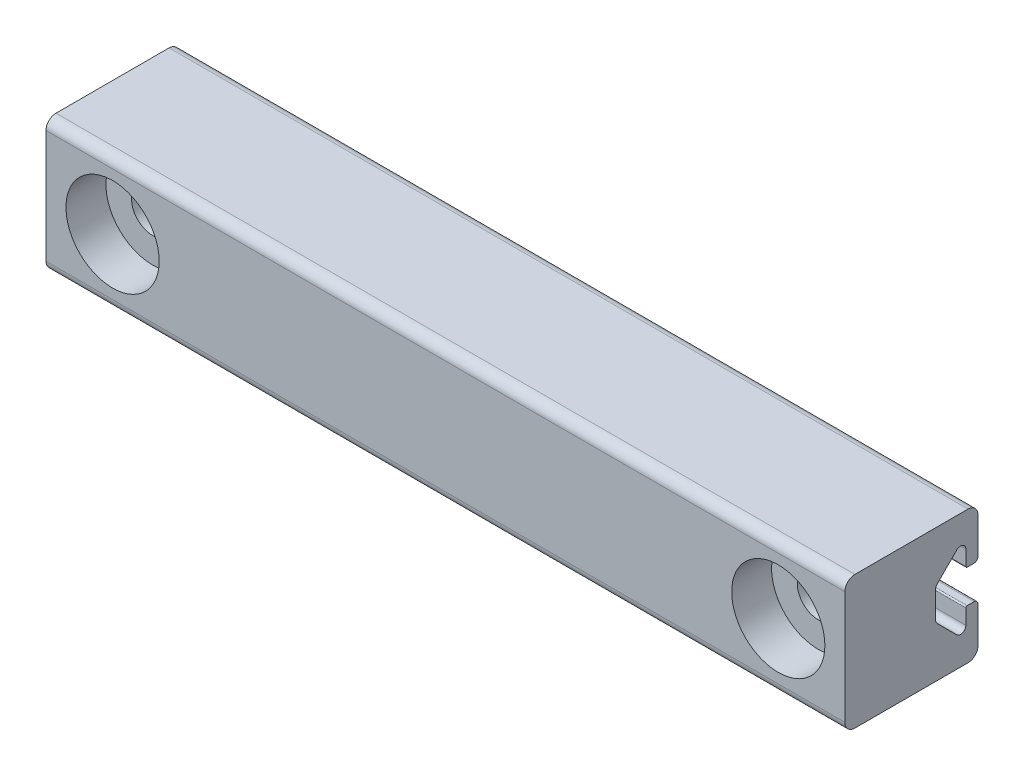
SolidWorks part; units mm, degrees
ref_plane "Front Plane" through (0, 0, 0) normal (0, 0, 1) x (1, 0, 0)
ref_plane "Top Plane" through (0, 0, 0) normal (0, 1, 0) x (1, 0, 0)
ref_plane "Right Plane" through (0, 0, 0) normal (1, 0, 0) x (0, 0, -1)
sketch "Sketch1" plane through (0, 0, 0) normal (1, 0, 0) x (0, 0, -1)
  line L0 (0, -10) -> (0, 10) construction
  line L1 (10, -10) -> (-10, -10)
  line L2 (10, -10) -> (10, 10)
  line L3 (10, 10) -> (0, 10)
  line L4 (-10, -10) -> (-10, 10)
  line L5 (10, -10) -> (-10, 10) construction
  line L6 (10, 10) -> (-10, -10) construction
  line L7 (10, 0) -> (-10, 0) construction
  line L8 (-2.5, 9.4) -> (-2.5, 8.3731)
  line L9 (-2.7, 8.1731) -> (-4.95, 8.1731)
  line L10 (-5.5157, 6.8075) -> (-2.6011, 3.8929)
  line L11 (-1.894, 3.6) -> (0, 3.6)
  line L12 (-5.3502, 4.0584) -> (-4.0584, 5.3502) construction
  line L13 (-3.825, 8.1731) -> (-3.825, 10) construction
  line L14 (-3.1, 10) -> (-10, 10)
  line L15 (-5.75, 7.3731) -> (5.75, 7.3731) construction
  circle A0 centre (0, 0) radius 2.15
  arc A1 (-4.95, 8.1731) -> (-5.5157, 6.8075) centre (-4.95, 7.3731) ccw
  arc A2 (-2.6011, 3.8929) -> (-1.894, 3.6) centre (-1.894, 4.6) ccw
  arc A3 (-2.5, 8.3731) -> (-2.7, 8.1731) centre (-2.7, 8.3731) cw
  arc A4 (-2.5, 9.4) -> (-3.1, 10) centre (-3.1, 9.4) ccw
  point P0 (0, 0)
  point P9 (0, 0)
  point P12 (0, 0)
  point P22 (-4.7043, 4.7043)
  point P32 (-2.5, 10)
  point P33 (-2.5, 8.8866)
  point P35 (-4.0584, 5.3502)
  point P37 (0, 7.3731)
  dimension "Center Hole Diameter" = 4.3
  dimension "D4" = 1
  dimension "D5" = 0.2
  dimension "D6" = 0.6
  dimension "D3" = 0.8
  dimension "Rail Height" = 20
  dimension "D7" = 6.4
  dimension "T Slot Width" = 5
  dimension "D10" = 10
  dimension "Rail Width" = 20
  dimension "D2" = 11.5
sketch "Sketch2" plane through (0, 0, 0) normal (0, 0, 1) x (1, 0, 0)
  line L0 (-132.4, 10) -> (-132.4, -10) construction
  line L1 (152.4, -10) -> (-152.4, -10) construction
  line L2 (152.4, -10) -> (152.4, 10) construction
  line L3 (152.4, 10) -> (-152.4, 10) construction
  line L4 (-152.4, -10) -> (-152.4, 10) construction
  line L5 (152.4, -10) -> (-152.4, 10) construction
  line L6 (152.4, 10) -> (-152.4, -10) construction
  line L7 (132.4, 10) -> (132.4, -10) construction
  point P0 (0, 0)
  point P12 (132.4, 0)
  dimension "Length" = 304.8
  dimension "D1" = 20
  dimension "D2" = 20
sketch "Sketch3" plane through (0, 0, 0) normal (1, 0, 0) x (0, 0, -1)
  line L0 (-5.5157, 6.8075) -> (-2.6011, 3.8929) construction
  line L5 (-3.1, 10) -> (-10, 10) construction
  line L6 (-2.5, 9.4) -> (-2.5, 8.3731) construction
  line L7 (-2.7, 8.1731) -> (-4.95, 8.1731) construction
  line L8 (-1.894, 3.6) -> (0, 3.6) construction
  line L9 (-5.5157, 6.8075) -> (-2.6011, 3.8929)
  line L10 (-10, 10) -> (0, 0) construction
  line L12 (-3.6, 1.894) -> (-3.6, 0)
  line L13 (-8.1731, 2.7) -> (-8.1731, 4.95)
  line L14 (-3.1, 10) -> (-8.5, 10)
  line L15 (-2.5, 9.4) -> (-2.5, 8.3731)
  line L16 (-2.7, 8.1731) -> (-4.95, 8.1731)
  line L17 (-1.894, 3.6) -> (0, 3.6)
  line L18 (-9.4, 2.5) -> (-8.3731, 2.5)
  line L19 (-10, 3.1) -> (-10, 8.5)
  line L20 (-6.8075, 5.5157) -> (-3.8929, 2.6011)
  line L21 (-3.6, 0) -> (-2.15, 0)
  line L22 (0, 3.6) -> (0, 2.15)
  arc A0 (-2.5, 9.4) -> (-3.1, 10) centre (-3.1, 9.4) ccw construction
  arc A1 (-2.7, 8.1731) -> (-2.5, 8.3731) centre (-2.7, 8.3731) ccw construction
  arc A2 (-4.95, 8.1731) -> (-5.5157, 6.8075) centre (-4.95, 7.3731) ccw construction
  arc A3 (-2.6011, 3.8929) -> (-1.894, 3.6) centre (-1.894, 4.6) ccw construction
  arc A4 (-2.5, 9.4) -> (-3.1, 10) centre (-3.1, 9.4) ccw
  arc A5 (-2.7, 8.1731) -> (-2.5, 8.3731) centre (-2.7, 8.3731) ccw
  arc A6 (-4.95, 8.1731) -> (-5.5157, 6.8075) centre (-4.95, 7.3731) ccw
  arc A7 (-2.6011, 3.8929) -> (-1.894, 3.6) centre (-1.894, 4.6) ccw
  arc A8 (-3.8929, 2.6011) -> (-3.6, 1.894) centre (-4.6, 1.894) cw
  arc A9 (-8.1731, 4.95) -> (-6.8075, 5.5157) centre (-7.3731, 4.95) cw
  arc A10 (-8.1731, 2.7) -> (-8.3731, 2.5) centre (-8.3731, 2.7) cw
  arc A11 (-9.4, 2.5) -> (-10, 3.1) centre (-9.4, 3.1) cw
  circle A12 centre (0, 0) radius 2.15 construction
  arc A13 (0, 2.15) -> (-2.15, 0) centre (0, 0) ccw
  arc A14 (-10, 8.5) -> (-8.5, 10) centre (-8.5, 8.5) cw
  dimension "D1" = 1.5
extrude "Boss-Extrude1" add sketch "Sketch3" against normal up to vertex (152.4 mm away) and the other way up to vertex (152.4 mm away) up to point (-152.4, 10, 0) other way up to point (152.4, 10, 0)
mirror "Mirror1" about plane through (0, 0, 0) normal (0, 1, 0) of bodies 104
mirror "Mirror2" about plane through (0, 0, 0) normal (0, 0, 1) of bodies 105
sketch "Sketch4" plane through (152.4, 0, 0) normal (1, 0, 0) x (0, 0, -1)
  line L36 (1.894, 3.6) -> (-1.894, 3.6)
  line L37 (-2.6011, 3.8929) -> (-5.5157, 6.8075)
  line L38 (-4.95, 8.1731) -> (-2.7, 8.1731)
  line L39 (-2.5, 8.3731) -> (-2.5, 9.4)
  line L40 (-3.1, 10) -> (-8.5, 10)
  line L41 (-10, 8.5) -> (-10, 3.1)
  line L42 (-9.4, 2.5) -> (-8.3731, 2.5)
  line L43 (-8.1731, 2.7) -> (-8.1731, 4.95)
  line L44 (-6.8075, 5.5157) -> (-3.8929, 2.6011)
  line L45 (-3.6, 1.894) -> (-3.6, -1.894)
  line L46 (-3.8929, -2.6011) -> (-6.8075, -5.5157)
  line L47 (-8.1731, -4.95) -> (-8.1731, -2.7)
  line L48 (-8.3731, -2.5) -> (-9.4, -2.5)
  line L49 (-10, -3.1) -> (-10, -8.5)
  line L50 (-8.5, -10) -> (-3.1, -10)
  line L51 (-2.5, -9.4) -> (-2.5, -8.3731)
  line L52 (-2.7, -8.1731) -> (-4.95, -8.1731)
  line L53 (-5.5157, -6.8075) -> (-2.6011, -3.8929)
  line L54 (-1.894, -3.6) -> (1.894, -3.6)
  line L55 (2.6011, -3.8929) -> (5.5157, -6.8075)
  line L56 (4.95, -8.1731) -> (2.7, -8.1731)
  line L57 (2.5, -8.3731) -> (2.5, -9.4)
  line L58 (3.1, -10) -> (8.5, -10)
  line L59 (10, -8.5) -> (10, -3.1)
  line L60 (9.4, -2.5) -> (8.3731, -2.5)
  line L61 (8.1731, -2.7) -> (8.1731, -4.95)
  line L62 (6.8075, -5.5157) -> (3.8929, -2.6011)
  line L63 (3.6, -1.894) -> (3.6, 1.894)
  line L64 (3.8929, 2.6011) -> (6.8075, 5.5157)
  line L65 (8.1731, 4.95) -> (8.1731, 2.7)
  line L66 (8.3731, 2.5) -> (9.4, 2.5)
  line L67 (10, 3.1) -> (10, 8.5)
  line L68 (8.5, 10) -> (3.1, 10)
  line L69 (2.5, 9.4) -> (2.5, 8.3731)
  line L70 (2.7, 8.1731) -> (4.95, 8.1731)
  line L71 (5.5157, 6.8075) -> (2.6011, 3.8929)
  line L72 (1.894, 3.6) -> (-1.894, 3.6)
  line L73 (-2.6011, 3.8929) -> (-5.5157, 6.8075)
  line L74 (-4.95, 8.1731) -> (-2.7, 8.1731)
  line L75 (-2.5, 8.3731) -> (-2.5, 9.4)
  line L76 (-3.1, 10) -> (-8.5, 10)
  line L77 (-10, 8.5) -> (-10, 3.1)
  line L78 (-9.4, 2.5) -> (-8.3731, 2.5)
  line L79 (-8.1731, 2.7) -> (-8.1731, 4.95)
  line L80 (-6.8075, 5.5157) -> (-3.8929, 2.6011)
  line L81 (-3.6, 1.894) -> (-3.6, -1.894)
  line L82 (-3.8929, -2.6011) -> (-6.8075, -5.5157)
  line L83 (-8.1731, -4.95) -> (-8.1731, -2.7)
  line L84 (-8.3731, -2.5) -> (-9.4, -2.5)
  line L85 (-10, -3.1) -> (-10, -8.5)
  line L86 (-8.5, -10) -> (-3.1, -10)
  line L87 (-2.5, -9.4) -> (-2.5, -8.3731)
  line L88 (-2.7, -8.1731) -> (-4.95, -8.1731)
  line L89 (-5.5157, -6.8075) -> (-2.6011, -3.8929)
  line L90 (-1.894, -3.6) -> (1.894, -3.6)
  line L91 (2.6011, -3.8929) -> (5.5157, -6.8075)
  line L92 (4.95, -8.1731) -> (2.7, -8.1731)
  line L93 (2.5, -8.3731) -> (2.5, -9.4)
  line L94 (3.1, -10) -> (8.5, -10)
  line L95 (10, -8.5) -> (10, -3.1)
  line L96 (9.4, -2.5) -> (8.3731, -2.5)
  line L97 (8.1731, -2.7) -> (8.1731, -4.95)
  line L98 (6.8075, -5.5157) -> (3.8929, -2.6011)
  line L99 (3.6, -1.894) -> (3.6, 1.894)
  line L100 (3.8929, 2.6011) -> (6.8075, 5.5157)
  line L101 (8.1731, 4.95) -> (8.1731, 2.7)
  line L102 (8.3731, 2.5) -> (9.4, 2.5)
  line L103 (10, 3.1) -> (10, 8.5)
  line L104 (8.5, 10) -> (3.1, 10)
  line L105 (2.5, 9.4) -> (2.5, 8.3731)
  line L106 (2.7, 8.1731) -> (4.95, 8.1731)
  line L107 (5.5157, 6.8075) -> (2.6011, 3.8929)
  circle A0 centre (0, 0) radius 2.15 construction
  circle A1 centre (0, 0) radius 2.15
  arc A36 (1.894, 3.6) -> (2.6011, 3.8929) centre (1.894, 4.6) ccw
  arc A37 (-2.6011, 3.8929) -> (-1.894, 3.6) centre (-1.894, 4.6) ccw
  arc A38 (-4.95, 8.1731) -> (-5.5157, 6.8075) centre (-4.95, 7.3731) ccw
  arc A39 (-2.7, 8.1731) -> (-2.5, 8.3731) centre (-2.7, 8.3731) ccw
  arc A40 (-2.5, 9.4) -> (-3.1, 10) centre (-3.1, 9.4) ccw
  arc A41 (-8.5, 10) -> (-10, 8.5) centre (-8.5, 8.5) ccw
  arc A42 (-10, 3.1) -> (-9.4, 2.5) centre (-9.4, 3.1) ccw
  arc A43 (-8.3731, 2.5) -> (-8.1731, 2.7) centre (-8.3731, 2.7) ccw
  arc A44 (-6.8075, 5.5157) -> (-8.1731, 4.95) centre (-7.3731, 4.95) ccw
  arc A45 (-3.6, 1.894) -> (-3.8929, 2.6011) centre (-4.6, 1.894) ccw
  arc A46 (-3.8929, -2.6011) -> (-3.6, -1.894) centre (-4.6, -1.894) ccw
  arc A47 (-8.1731, -4.95) -> (-6.8075, -5.5157) centre (-7.3731, -4.95) ccw
  arc A48 (-8.1731, -2.7) -> (-8.3731, -2.5) centre (-8.3731, -2.7) ccw
  arc A49 (-9.4, -2.5) -> (-10, -3.1) centre (-9.4, -3.1) ccw
  arc A50 (-10, -8.5) -> (-8.5, -10) centre (-8.5, -8.5) ccw
  arc A51 (-3.1, -10) -> (-2.5, -9.4) centre (-3.1, -9.4) ccw
  arc A52 (-2.5, -8.3731) -> (-2.7, -8.1731) centre (-2.7, -8.3731) ccw
  arc A53 (-5.5157, -6.8075) -> (-4.95, -8.1731) centre (-4.95, -7.3731) ccw
  arc A54 (-1.894, -3.6) -> (-2.6011, -3.8929) centre (-1.894, -4.6) ccw
  arc A55 (2.6011, -3.8929) -> (1.894, -3.6) centre (1.894, -4.6) ccw
  arc A56 (4.95, -8.1731) -> (5.5157, -6.8075) centre (4.95, -7.3731) ccw
  arc A57 (2.7, -8.1731) -> (2.5, -8.3731) centre (2.7, -8.3731) ccw
  arc A58 (2.5, -9.4) -> (3.1, -10) centre (3.1, -9.4) ccw
  arc A59 (8.5, -10) -> (10, -8.5) centre (8.5, -8.5) ccw
  arc A60 (10, -3.1) -> (9.4, -2.5) centre (9.4, -3.1) ccw
  arc A61 (8.3731, -2.5) -> (8.1731, -2.7) centre (8.3731, -2.7) ccw
  arc A62 (6.8075, -5.5157) -> (8.1731, -4.95) centre (7.3731, -4.95) ccw
  arc A63 (3.6, -1.894) -> (3.8929, -2.6011) centre (4.6, -1.894) ccw
  arc A64 (3.8929, 2.6011) -> (3.6, 1.894) centre (4.6, 1.894) ccw
  arc A65 (8.1731, 4.95) -> (6.8075, 5.5157) centre (7.3731, 4.95) ccw
  arc A66 (8.1731, 2.7) -> (8.3731, 2.5) centre (8.3731, 2.7) ccw
  arc A67 (9.4, 2.5) -> (10, 3.1) centre (9.4, 3.1) ccw
  arc A68 (10, 8.5) -> (8.5, 10) centre (8.5, 8.5) ccw
  arc A69 (3.1, 10) -> (2.5, 9.4) centre (3.1, 9.4) ccw
  arc A70 (2.5, 8.3731) -> (2.7, 8.1731) centre (2.7, 8.3731) ccw
  arc A71 (5.5157, 6.8075) -> (4.95, 8.1731) centre (4.95, 7.3731) ccw
  arc A72 (1.894, 3.6) -> (2.6011, 3.8929) centre (1.894, 4.6) ccw
  arc A73 (-2.6011, 3.8929) -> (-1.894, 3.6) centre (-1.894, 4.6) ccw
  arc A74 (-4.95, 8.1731) -> (-5.5157, 6.8075) centre (-4.95, 7.3731) ccw
  arc A75 (-2.7, 8.1731) -> (-2.5, 8.3731) centre (-2.7, 8.3731) ccw
  arc A76 (-2.5, 9.4) -> (-3.1, 10) centre (-3.1, 9.4) ccw
  arc A77 (-8.5, 10) -> (-10, 8.5) centre (-8.5, 8.5) ccw
  arc A78 (-10, 3.1) -> (-9.4, 2.5) centre (-9.4, 3.1) ccw
  arc A79 (-8.3731, 2.5) -> (-8.1731, 2.7) centre (-8.3731, 2.7) ccw
  arc A80 (-6.8075, 5.5157) -> (-8.1731, 4.95) centre (-7.3731, 4.95) ccw
  arc A81 (-3.6, 1.894) -> (-3.8929, 2.6011) centre (-4.6, 1.894) ccw
  arc A82 (-3.8929, -2.6011) -> (-3.6, -1.894) centre (-4.6, -1.894) ccw
  arc A83 (-8.1731, -4.95) -> (-6.8075, -5.5157) centre (-7.3731, -4.95) ccw
  arc A84 (-8.1731, -2.7) -> (-8.3731, -2.5) centre (-8.3731, -2.7) ccw
  arc A85 (-9.4, -2.5) -> (-10, -3.1) centre (-9.4, -3.1) ccw
  arc A86 (-10, -8.5) -> (-8.5, -10) centre (-8.5, -8.5) ccw
  arc A87 (-3.1, -10) -> (-2.5, -9.4) centre (-3.1, -9.4) ccw
  arc A88 (-2.5, -8.3731) -> (-2.7, -8.1731) centre (-2.7, -8.3731) ccw
  arc A89 (-5.5157, -6.8075) -> (-4.95, -8.1731) centre (-4.95, -7.3731) ccw
  arc A90 (-1.894, -3.6) -> (-2.6011, -3.8929) centre (-1.894, -4.6) ccw
  arc A91 (2.6011, -3.8929) -> (1.894, -3.6) centre (1.894, -4.6) ccw
  arc A92 (4.95, -8.1731) -> (5.5157, -6.8075) centre (4.95, -7.3731) ccw
  arc A93 (2.7, -8.1731) -> (2.5, -8.3731) centre (2.7, -8.3731) ccw
  arc A94 (2.5, -9.4) -> (3.1, -10) centre (3.1, -9.4) ccw
  arc A95 (8.5, -10) -> (10, -8.5) centre (8.5, -8.5) ccw
  arc A96 (10, -3.1) -> (9.4, -2.5) centre (9.4, -3.1) ccw
  arc A97 (8.3731, -2.5) -> (8.1731, -2.7) centre (8.3731, -2.7) ccw
  arc A98 (6.8075, -5.5157) -> (8.1731, -4.95) centre (7.3731, -4.95) ccw
  arc A99 (3.6, -1.894) -> (3.8929, -2.6011) centre (4.6, -1.894) ccw
  arc A100 (3.8929, 2.6011) -> (3.6, 1.894) centre (4.6, 1.894) ccw
  arc A101 (8.1731, 4.95) -> (6.8075, 5.5157) centre (7.3731, 4.95) ccw
  arc A102 (8.1731, 2.7) -> (8.3731, 2.5) centre (8.3731, 2.7) ccw
  arc A103 (9.4, 2.5) -> (10, 3.1) centre (9.4, 3.1) ccw
  arc A104 (10, 8.5) -> (8.5, 10) centre (8.5, 8.5) ccw
  arc A105 (3.1, 10) -> (2.5, 9.4) centre (3.1, 9.4) ccw
  arc A106 (2.5, 8.3731) -> (2.7, 8.1731) centre (2.7, 8.3731) ccw
  arc A107 (5.5157, 6.8075) -> (4.95, 8.1731) centre (4.95, 7.3731) ccw
  dimension "D1" = 0
extrude "Boss-Extrude2" add sketch "Sketch4" along normal offset from surface (95.2 mm away) 400 up to face at (-152.4, 0, 0)
sketch "Sketch5" plane through (247.6, 0, 0) normal (1, 0, 0) x (0, 0, -1)
  line L1 (-15, -15) -> (15, -15)
  line L2 (-15, -15) -> (-15, 15)
  line L3 (-15, 15) -> (15, 15)
  line L4 (15, -15) -> (15, 15)
  line L5 (-15, -15) -> (15, 15) construction
  line L6 (-15, 15) -> (15, -15) construction
  point P0 (0, 0)
  dimension "D1" = 30
extrude "Cut-Extrude1" cut sketch "Sketch5" against normal offset from surface (280 mm away) 120 up to face at (-152.4, 0, 0)
sketch "Sketch6" plane through (-32.4, 0, 0) normal (1, 0, 0) x (0, 0, -1)
  line L1 (10, -10) -> (-10, -10)
  line L2 (10, -10) -> (10, 10)
  line L3 (10, 10) -> (-10, 10)
  line L4 (-10, -10) -> (-10, 10)
  line L5 (10, -10) -> (-10, 10) construction
  line L6 (10, 10) -> (-10, -10) construction
  line L7 (-8.5, 10) -> (-3.1, 10) construction
  line L8 (-10, 3.1) -> (-10, 8.5) construction
  point P0 (0, 0)
ref_plane "Plane1" through (-92.4, 0, 0) normal (-1, 0, 0) x (0, 0, 1)
sketch "Sketch8" plane through (-32.4, 0, 0) normal (1, 0, 0) x (0, 0, -1)
  line L0 (-8.5, 10) -> (8.5, 10)
  line L1 (-10, 8.5) -> (-10, -8.5)
  line L3 (-8.5, -10) -> (8.5, -10)
  line L36 (-2.5, 8.3731) -> (-2.5, 9.4)
  line L37 (-3.1, 10) -> (-8.5, 10)
  line L38 (-10, 8.5) -> (-10, 3.1)
  line L39 (-9.4, 2.5) -> (-8.3731, 2.5)
  line L40 (-8.1731, 2.7) -> (-8.1731, 4.95)
  line L41 (-6.8075, 5.5157) -> (-3.8929, 2.6011)
  line L42 (-3.6, 1.894) -> (-3.6, -1.894)
  line L43 (-3.8929, -2.6011) -> (-6.8075, -5.5157)
  line L44 (-8.1731, -4.95) -> (-8.1731, -2.7)
  line L45 (-8.3731, -2.5) -> (-9.4, -2.5)
  line L46 (-10, -3.1) -> (-10, -8.5)
  line L47 (-8.5, -10) -> (-3.1, -10)
  line L48 (-2.5, -9.4) -> (-2.5, -8.3731)
  line L49 (-2.7, -8.1731) -> (-4.95, -8.1731)
  line L50 (-5.5157, -6.8075) -> (-2.6011, -3.8929)
  line L51 (-1.894, -3.6) -> (1.894, -3.6)
  line L52 (2.6011, -3.8929) -> (5.5157, -6.8075)
  line L53 (4.95, -8.1731) -> (2.7, -8.1731)
  line L54 (2.5, -8.3731) -> (2.5, -9.4)
  line L55 (3.1, -10) -> (8.5, -10)
  line L56 (10, -8.5) -> (10, -3.1)
  line L57 (9.4, -2.5) -> (8.3731, -2.5)
  line L58 (8.1731, -2.7) -> (8.1731, -4.95)
  line L59 (6.8075, -5.5157) -> (3.8929, -2.6011)
  line L60 (3.6, -1.894) -> (3.6, 1.894)
  line L61 (3.8929, 2.6011) -> (6.8075, 5.5157)
  line L62 (8.1731, 4.95) -> (8.1731, 2.7)
  line L63 (8.3731, 2.5) -> (9.4, 2.5)
  line L64 (10, 3.1) -> (10, 8.5)
  line L65 (8.5, 10) -> (3.1, 10)
  line L66 (2.5, 9.4) -> (2.5, 8.3731)
  line L67 (2.7, 8.1731) -> (4.95, 8.1731)
  line L68 (5.5157, 6.8075) -> (2.6011, 3.8929)
  line L69 (1.894, 3.6) -> (-1.894, 3.6)
  line L70 (-2.6011, 3.8929) -> (-5.5157, 6.8075)
  line L71 (-4.95, 8.1731) -> (-2.7, 8.1731)
  line L92 (10, -8.5) -> (10, -3.1)
  line L93 (9.4, -2.5) -> (8.3731, -2.5)
  line L94 (8.1731, -2.7) -> (8.1731, -4.95)
  line L95 (6.8075, -5.5157) -> (3.8929, -2.6011)
  line L96 (3.6, -1.894) -> (3.6, 1.894)
  line L97 (3.8929, 2.6011) -> (6.8075, 5.5157)
  line L98 (8.1731, 4.95) -> (8.1731, 2.7)
  line L99 (8.3731, 2.5) -> (9.4, 2.5)
  line L100 (10, 3.1) -> (10, 8.5)
  arc A1 (-10, -8.5) -> (-8.5, -10) centre (-8.5, -8.5) ccw construction
  arc A2 (-10, -8.5) -> (-8.5, -10) centre (-8.5, -8.5) ccw
  arc A36 (-2.7, 8.1731) -> (-2.5, 8.3731) centre (-2.7, 8.3731) ccw
  arc A37 (-2.5, 9.4) -> (-3.1, 10) centre (-3.1, 9.4) ccw
  arc A38 (-8.5, 10) -> (-10, 8.5) centre (-8.5, 8.5) ccw
  arc A39 (-10, 3.1) -> (-9.4, 2.5) centre (-9.4, 3.1) ccw
  arc A40 (-8.3731, 2.5) -> (-8.1731, 2.7) centre (-8.3731, 2.7) ccw
  arc A41 (-6.8075, 5.5157) -> (-8.1731, 4.95) centre (-7.3731, 4.95) ccw
  arc A42 (-3.6, 1.894) -> (-3.8929, 2.6011) centre (-4.6, 1.894) ccw
  arc A43 (-3.8929, -2.6011) -> (-3.6, -1.894) centre (-4.6, -1.894) ccw
  arc A44 (-8.1731, -4.95) -> (-6.8075, -5.5157) centre (-7.3731, -4.95) ccw
  arc A45 (-8.1731, -2.7) -> (-8.3731, -2.5) centre (-8.3731, -2.7) ccw
  arc A46 (-9.4, -2.5) -> (-10, -3.1) centre (-9.4, -3.1) ccw
  arc A47 (-10, -8.5) -> (-8.5, -10) centre (-8.5, -8.5) ccw
  arc A48 (-3.1, -10) -> (-2.5, -9.4) centre (-3.1, -9.4) ccw
  arc A49 (-2.5, -8.3731) -> (-2.7, -8.1731) centre (-2.7, -8.3731) ccw
  arc A50 (-5.5157, -6.8075) -> (-4.95, -8.1731) centre (-4.95, -7.3731) ccw
  arc A51 (-1.894, -3.6) -> (-2.6011, -3.8929) centre (-1.894, -4.6) ccw
  arc A52 (2.6011, -3.8929) -> (1.894, -3.6) centre (1.894, -4.6) ccw
  arc A53 (4.95, -8.1731) -> (5.5157, -6.8075) centre (4.95, -7.3731) ccw
  arc A54 (2.7, -8.1731) -> (2.5, -8.3731) centre (2.7, -8.3731) ccw
  arc A55 (2.5, -9.4) -> (3.1, -10) centre (3.1, -9.4) ccw
  arc A56 (8.5, -10) -> (10, -8.5) centre (8.5, -8.5) ccw
  arc A57 (10, -3.1) -> (9.4, -2.5) centre (9.4, -3.1) ccw
  arc A58 (8.3731, -2.5) -> (8.1731, -2.7) centre (8.3731, -2.7) ccw
  arc A59 (6.8075, -5.5157) -> (8.1731, -4.95) centre (7.3731, -4.95) ccw
  arc A60 (3.6, -1.894) -> (3.8929, -2.6011) centre (4.6, -1.894) ccw
  arc A61 (3.8929, 2.6011) -> (3.6, 1.894) centre (4.6, 1.894) ccw
  arc A62 (8.1731, 4.95) -> (6.8075, 5.5157) centre (7.3731, 4.95) ccw
  arc A63 (8.1731, 2.7) -> (8.3731, 2.5) centre (8.3731, 2.7) ccw
  arc A64 (9.4, 2.5) -> (10, 3.1) centre (9.4, 3.1) ccw
  arc A65 (10, 8.5) -> (8.5, 10) centre (8.5, 8.5) ccw
  arc A66 (3.1, 10) -> (2.5, 9.4) centre (3.1, 9.4) ccw
  arc A67 (2.5, 8.3731) -> (2.7, 8.1731) centre (2.7, 8.3731) ccw
  arc A68 (5.5157, 6.8075) -> (4.95, 8.1731) centre (4.95, 7.3731) ccw
  arc A69 (1.894, 3.6) -> (2.6011, 3.8929) centre (1.894, 4.6) ccw
  arc A70 (-2.6011, 3.8929) -> (-1.894, 3.6) centre (-1.894, 4.6) ccw
  arc A71 (-4.95, 8.1731) -> (-5.5157, 6.8075) centre (-4.95, 7.3731) ccw
  arc A74 (-8.5, 10) -> (-10, 8.5) centre (-8.5, 8.5) ccw
  arc A92 (8.5, -10) -> (10, -8.5) centre (8.5, -8.5) ccw
  arc A93 (10, -3.1) -> (9.4, -2.5) centre (9.4, -3.1) ccw
  arc A94 (8.3731, -2.5) -> (8.1731, -2.7) centre (8.3731, -2.7) ccw
  arc A95 (6.8075, -5.5157) -> (8.1731, -4.95) centre (7.3731, -4.95) ccw
  arc A96 (3.6, -1.894) -> (3.8929, -2.6011) centre (4.6, -1.894) ccw
  arc A97 (3.8929, 2.6011) -> (3.6, 1.894) centre (4.6, 1.894) ccw
  arc A98 (8.1731, 4.95) -> (6.8075, 5.5157) centre (7.3731, 4.95) ccw
  arc A99 (8.1731, 2.7) -> (8.3731, 2.5) centre (8.3731, 2.7) ccw
  arc A100 (9.4, 2.5) -> (10, 3.1) centre (9.4, 3.1) ccw
  arc A101 (10, 8.5) -> (8.5, 10) centre (8.5, 8.5) ccw
  dimension "D1" = 0
extrude "Boss-Extrude5" add sketch "Sketch8" against normal up to surface (120 mm away) up to face at (-152.4, 0, 0)
sketch "Sketch9" plane through (0, 0, 10) normal (0, 0, 1) x (1, 0, 0)
  line L0 (-92.4, 10) -> (-92.4, 0) construction
  line L1 (-152.4, 10) -> (-32.4, 10) construction
  line L2 (-92.4, 0) -> (-42.4, 0) construction
  line L3 (-92.4, 0) -> (-142.4, 0) construction
  circle A0 centre (-142.4, 0) radius 3.15
  circle A1 centre (-42.4, 0) radius 3.15
  dimension "D2" = 6.3
  dimension "D1" = 100
extrude "Cut-Extrude2" cut sketch "Sketch9" against normal through all
sketch "Sketch10" plane through (0, 0, 10) normal (0, 0, 1) x (1, 0, 0)
  circle A0 centre (-142.4, 0) radius 7
  circle A1 centre (-42.4, 0) radius 7
  dimension "D1" = 14
extrude "Cut-Extrude3" cut sketch "Sketch10" against normal blind 6
equation "\"D10@Sketch1\" = \"Rail Height@Sketch1\" / 2"
equation "\"D2@Sketch2\"=\"D1@Sketch2\""
